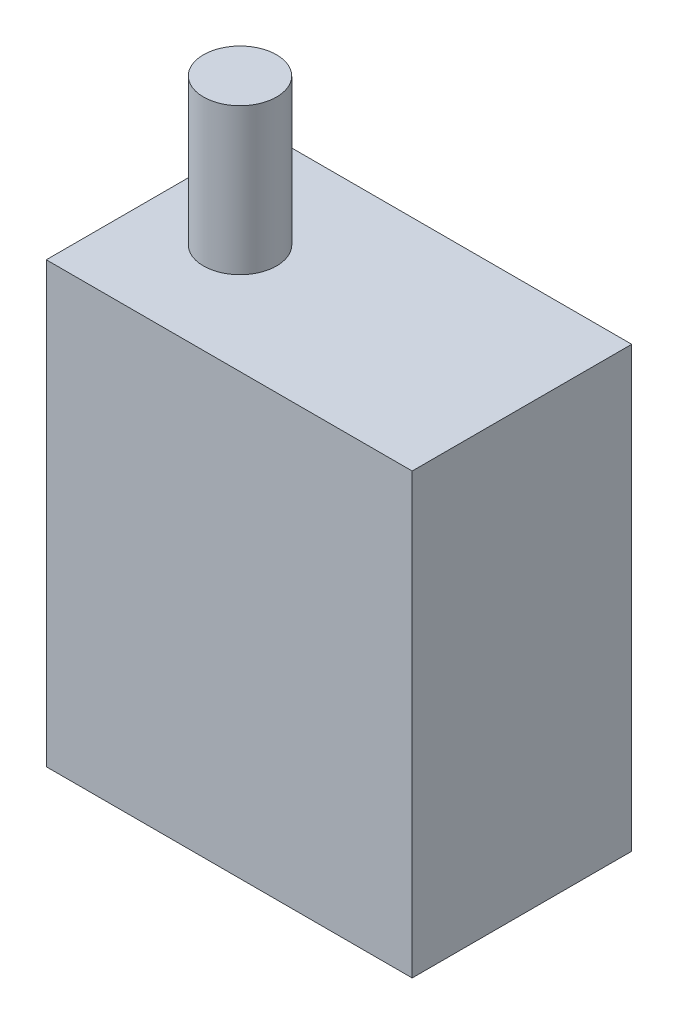
SolidWorks part; units mm, degrees
ref_plane "Front Plane" through (0, 0, 0) normal (0, 0, 1) x (1, 0, 0)
ref_plane "Top Plane" through (0, 0, 0) normal (0, 1, 0) x (1, 0, 0)
ref_plane "Right Plane" through (0, 0, 0) normal (1, 0, 0) x (0, 0, -1)
sketch "Sketch1" plane through (0, 0, 0) normal (0, 1, 0) x (1, 0, 0)
  line L1 (0, 0) -> (-25, 0)
  line L2 (0, 0) -> (0, 15)
  line L3 (0, 15) -> (-25, 15)
  line L4 (-25, 0) -> (-25, 15)
  dimension "D1" = 25
  dimension "D2" = 15
extrude "Boss-Extrude1" add sketch "Sketch1" along normal blind 30
sketch "Sketch2" plane through (0, 30, 0) normal (0, 1, 0) x (1, 0, 0)
  circle A0 centre (-19.2632, 7.5) radius 2.5
  dimension "D1" = 5
extrude "Boss-Extrude2" add sketch "Sketch2" along normal blind 10
